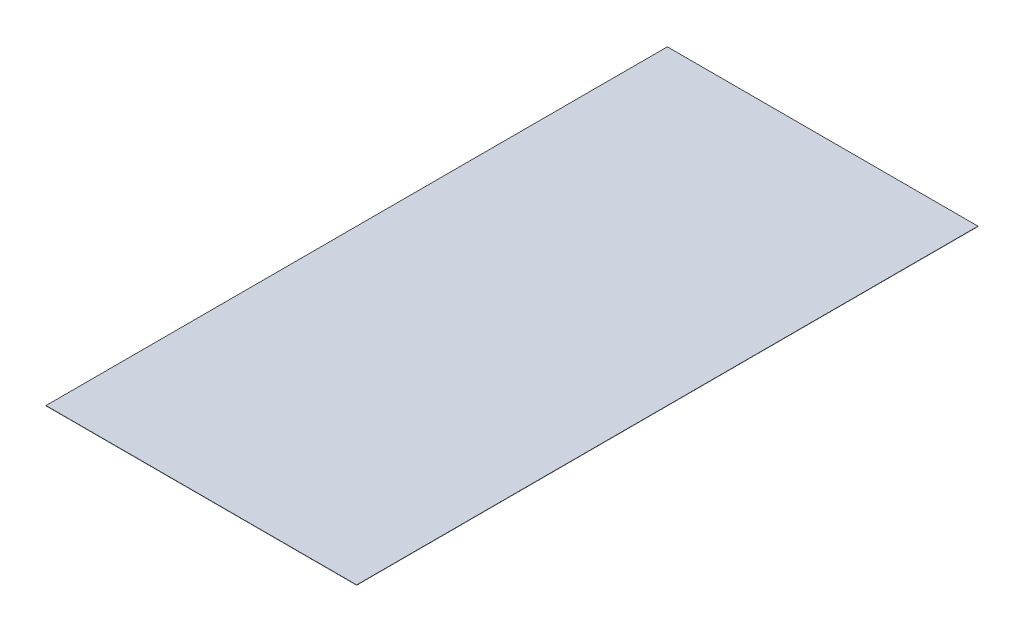
SolidWorks part; units mm, degrees
ref_plane "Plan de face" through (0, 0, 0) normal (0, 0, 1) x (1, 0, 0)
ref_plane "Plan de dessus" through (0, 0, 0) normal (0, 1, 0) x (1, 0, 0)
ref_plane "Plan de droite" through (0, 0, 0) normal (1, 0, 0) x (0, 0, -1)
sketch "Esquisse1" plane through (0, 0, 0) normal (0, 1, 0) x (1, 0, 0)
  line L1 (-625, -1250) -> (625, -1250)
  line L2 (-625, -1250) -> (-625, 1250)
  line L3 (-625, 1250) -> (625, 1250)
  line L4 (625, -1250) -> (625, 1250)
  line L5 (-625, -1250) -> (625, 1250) construction
  line L6 (-625, 1250) -> (625, -1250) construction
  point P0 (0, 0)
  dimension "D1" = 1250
  dimension "D2" = 2500
extrude "Boss.-Extru.1" add sketch "Esquisse1" along normal blind 1
